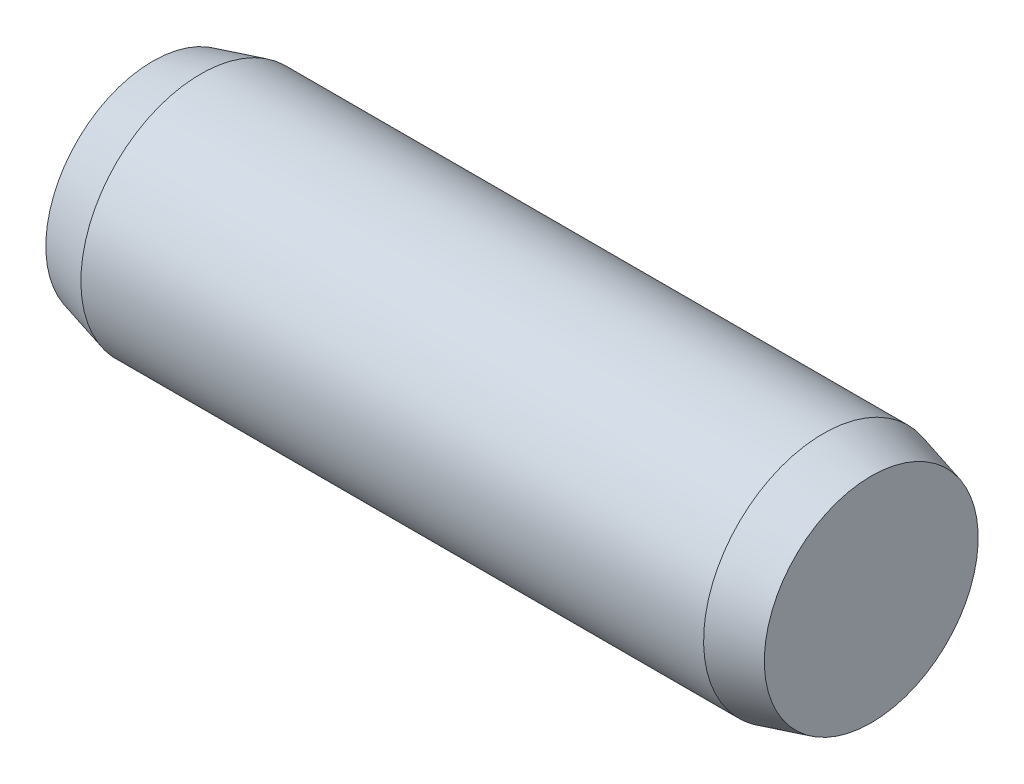
SolidWorks part; units mm, degrees
ref_plane "Plane1" through (0, 0, 0) normal (0, 0, 1) x (1, 0, 0)
ref_plane "Plane2" through (0, 0, 0) normal (0, 1, 0) x (1, 0, 0)
ref_plane "Plane3" through (0, 0, 0) normal (1, 0, 0) x (0, 0, -1)
sketch "BodySke" plane through (0, 0, 0) normal (0, 0, 1) x (1, 0, 0)
  line L0 (0, 0) -> (40.9091, 0) construction
  line L1 (28, 5) -> (30, 4.4641)
  line L2 (2, 5) -> (28, 5)
  line L3 (30, 4.4641) -> (30, 0)
  line L4 (0, 0) -> (30, 0)
  line L5 (2, 5) -> (0, 4.4641)
  line L6 (0, 4.4641) -> (0, 0)
  dimension "D1" = 15
  dimension "Diameter" = 10
  dimension "Length" = 30
  dimension "Chamfer_len" = 2
revolve "Body" add sketch "BodySke" angle 360 about L0
